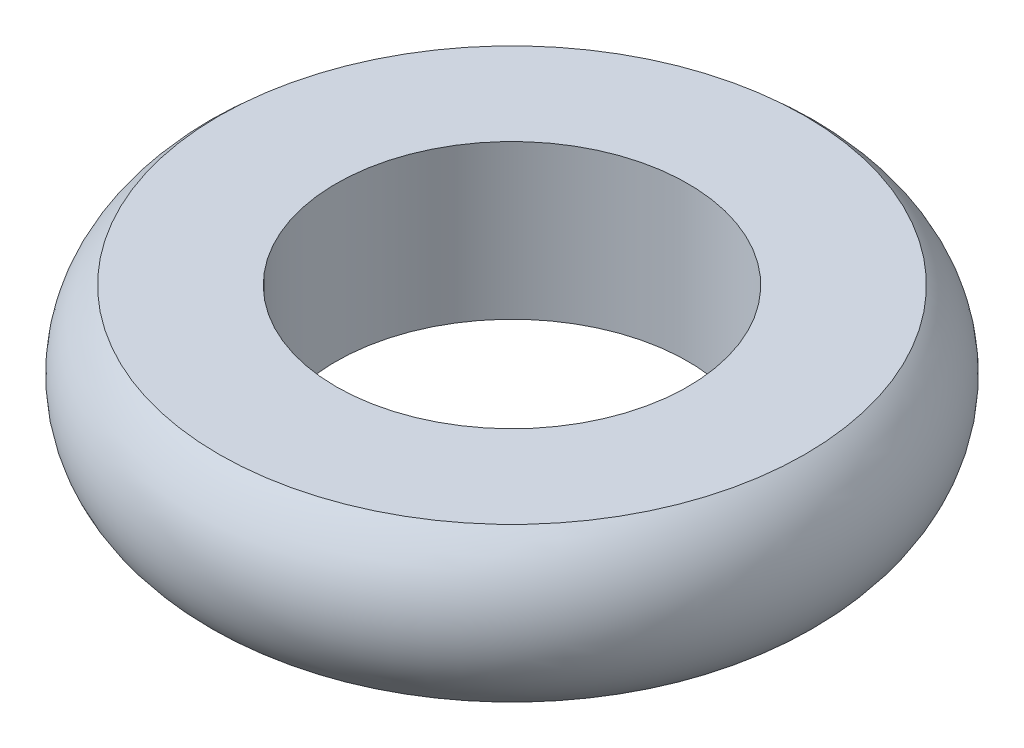
SolidWorks part; units mm, degrees
ref_plane "Front Plane" through (0, 0, 0) normal (0, 0, 1) x (1, 0, 0)
ref_plane "Top Plane" through (0, 0, 0) normal (0, 1, 0) x (1, 0, 0)
ref_plane "Right Plane" through (0, 0, 0) normal (1, 0, 0) x (0, 0, -1)
sketch "Sketch1" plane through (0, 0, 0) normal (0, 0, 1) x (1, 0, 0)
  line L0 (0, 0) -> (0, 2.8414) construction
  line L1 (0, 0) -> (-2.1, 0) construction
  line L2 (-2.1, 0) -> (-2.1, 0.7) construction
  line L3 (-2.1, 0.7) -> (-1.5343, 0.7)
  line L4 (-2.1, 0.7) -> (-2.6657, 0.7)
  line L5 (-2.1, -0.7) -> (-2.6657, -0.7)
  line L6 (-2.1, -0.7) -> (-1.5343, -0.7)
  arc A0 (-2.6657, 0.7) -> (-2.6657, -0.7) centre (-2.1, 0) ccw
  arc A1 (-1.5343, -0.7) -> (-1.5343, 0.7) centre (-2.1, 0) ccw
  dimension "D2" = 1.8
  dimension "D1" = 2.1
  dimension "D3" = 0.7
revolve "Revolve1" add sketch "Sketch1" angle 360 about L0
ref_plane "Plane1" through (0, 2, 0) normal (0, 1, 0) x (1, 0, 0)
sketch "Sketch3" plane through (0, 2, 0) normal (0, 1, 0) x (1, 0, 0)
  circle A0 centre (0, 0) radius 1.6
  dimension "D1" = 3.2
extrude "Cut-Extrude2" cut sketch "Sketch3" against normal blind 5.2
